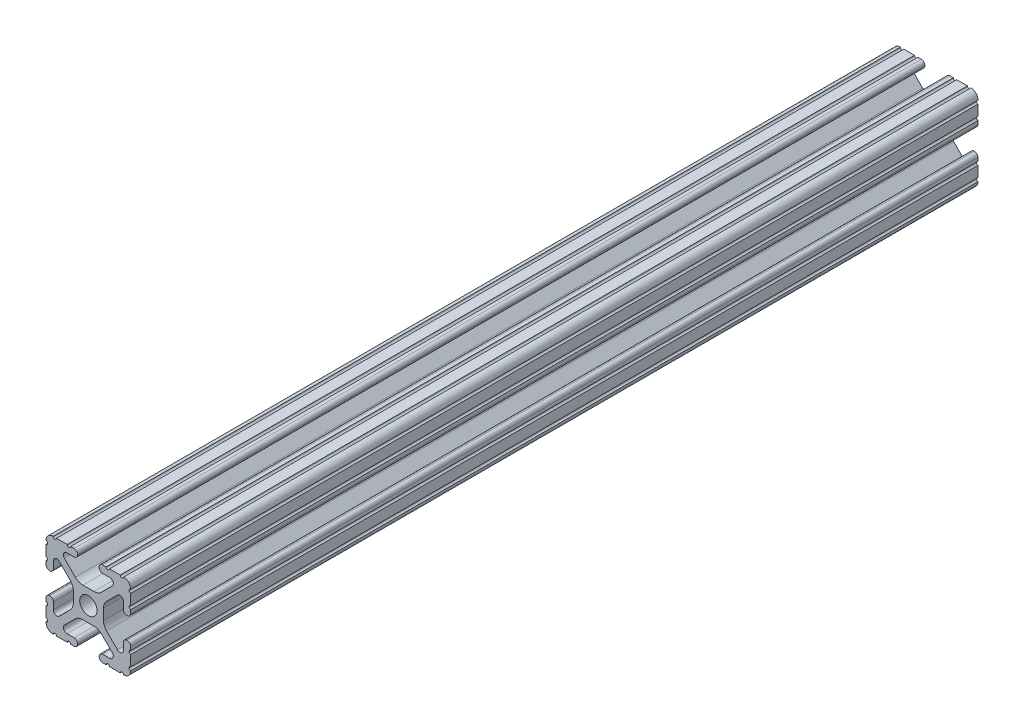
SolidWorks part; units mm, degrees
ref_plane "Front Plane" through (0, 0, 0) normal (0, 0, 1) x (1, 0, 0)
ref_plane "Top Plane" through (0, 0, 0) normal (0, 1, 0) x (1, 0, 0)
ref_plane "Right Plane" through (0, 0, 0) normal (1, 0, 0) x (0, 0, -1)
sketch "Sketch1" plane through (0, 0, 0) normal (0, 0, 1) x (1, 0, 0)
  line L88 (-7.1797, -8.6452) -> (-3.9523, -5.4237)
  line L89 (-1.7093, -4.4958) -> (1.7093, -4.4958)
  line L90 (3.9523, -5.4237) -> (7.1797, -8.6452)
  line L91 (6.4164, -10.4902) -> (4.2875, -10.4902)
  line L92 (3.2385, -11.5392) -> (3.2385, -11.651)
  line L93 (4.2875, -12.7) -> (5.3171, -12.7)
  line L94 (6.3331, -12.7) -> (9.5504, -12.7)
  line L95 (12.7, -9.5504) -> (12.7, -6.3331)
  line L96 (12.7, -5.3171) -> (12.7, -4.2875)
  line L97 (11.651, -3.2385) -> (11.5392, -3.2385)
  line L98 (10.4902, -4.2875) -> (10.4902, -6.4021)
  line L99 (8.7371, -7.1294) -> (5.441, -3.8408)
  line L100 (4.5085, -1.5932) -> (4.5085, 1.5932)
  line L101 (5.441, 3.8408) -> (8.7371, 7.1294)
  line L102 (10.4902, 6.4021) -> (10.4902, 4.2875)
  line L103 (11.5392, 3.2385) -> (11.651, 3.2385)
  line L104 (12.7, 4.2875) -> (12.7, 5.3171)
  line L105 (12.7, 6.3331) -> (12.7, 9.5504)
  line L106 (9.5504, 12.7) -> (6.3331, 12.7)
  line L107 (5.3171, 12.7) -> (4.2875, 12.7)
  line L108 (3.2385, 11.651) -> (3.2385, 11.5392)
  line L109 (4.2875, 10.4902) -> (6.4768, 10.4902)
  line L110 (7.207, 8.7244) -> (3.8983, 5.4232)
  line L111 (1.6558, 4.4958) -> (-1.6558, 4.4958)
  line L112 (-3.8983, 5.4232) -> (-7.207, 8.7244)
  line L113 (-6.4768, 10.4902) -> (-4.2875, 10.4902)
  line L114 (-3.2385, 11.5392) -> (-3.2385, 11.651)
  line L115 (-4.2875, 12.7) -> (-5.3171, 12.7)
  line L116 (-6.3331, 12.7) -> (-9.5504, 12.7)
  line L117 (-12.7, 9.5504) -> (-12.7, 6.3331)
  line L118 (-12.7, 5.3171) -> (-12.7, 4.2875)
  line L119 (-11.651, 3.2385) -> (-11.5392, 3.2385)
  line L120 (-10.4902, 4.2875) -> (-10.4902, 6.4021)
  line L121 (-8.7371, 7.1294) -> (-5.441, 3.8408)
  line L122 (-4.5085, 1.5932) -> (-4.5085, -1.5932)
  line L123 (-5.441, -3.8408) -> (-8.7371, -7.1294)
  line L124 (-10.4902, -6.4021) -> (-10.4902, -4.2875)
  line L125 (-11.5392, -3.2385) -> (-11.651, -3.2385)
  line L126 (-12.7, -4.2875) -> (-12.7, -5.3171)
  line L127 (-12.7, -6.3331) -> (-12.7, -9.5504)
  line L128 (-9.5504, -12.7) -> (-6.3331, -12.7)
  line L129 (-5.3171, -12.7) -> (-4.2875, -12.7)
  line L130 (-3.2385, -11.651) -> (-3.2385, -11.5392)
  line L131 (-4.2875, -10.4902) -> (-6.4164, -10.4902)
  circle A1 centre (0, 0) radius 2.6035
  arc A104 (-7.1797, -8.6452) -> (-6.4164, -10.4902) centre (-6.4164, -9.4098) ccw
  arc A105 (-1.7093, -4.4958) -> (-3.9523, -5.4237) centre (-1.7093, -7.6708) ccw
  arc A106 (3.9523, -5.4237) -> (1.7093, -4.4958) centre (1.7093, -7.6708) ccw
  arc A107 (6.4164, -10.4902) -> (7.1797, -8.6452) centre (6.4164, -9.4098) ccw
  arc A108 (4.2875, -10.4902) -> (3.2385, -11.5392) centre (4.2875, -11.5392) ccw
  arc A109 (3.2385, -11.651) -> (4.2875, -12.7) centre (4.2875, -11.651) ccw
  arc A110 (6.3331, -12.7) -> (5.3171, -12.7) centre (5.8251, -12.7) ccw
  arc A111 (10.5664, -12.6998) -> (9.5504, -12.7) centre (10.0584, -12.7) ccw
  arc A112 (10.5664, -12.6998) -> (12.6998, -10.5664) centre (10.5918, -10.5918) ccw
  arc A113 (12.7, -9.5504) -> (12.6998, -10.5664) centre (12.7, -10.0584) ccw
  arc A114 (12.7, -5.3171) -> (12.7, -6.3331) centre (12.7, -5.8251) ccw
  arc A115 (12.7, -4.2875) -> (11.651, -3.2385) centre (11.651, -4.2875) ccw
  arc A116 (11.5392, -3.2385) -> (10.4902, -4.2875) centre (11.5392, -4.2875) ccw
  arc A117 (8.7371, -7.1294) -> (10.4902, -6.4021) centre (9.4628, -6.4021) ccw
  arc A118 (4.5085, -1.5932) -> (5.441, -3.8408) centre (7.6835, -1.5932) ccw
  arc A119 (5.441, 3.8408) -> (4.5085, 1.5932) centre (7.6835, 1.5932) ccw
  arc A120 (10.4902, 6.4021) -> (8.7371, 7.1294) centre (9.4628, 6.4021) ccw
  arc A121 (10.4902, 4.2875) -> (11.5392, 3.2385) centre (11.5392, 4.2875) ccw
  arc A122 (11.651, 3.2385) -> (12.7, 4.2875) centre (11.651, 4.2875) ccw
  arc A123 (12.7, 6.3331) -> (12.7, 5.3171) centre (12.7, 5.8251) ccw
  arc A124 (12.6998, 10.5664) -> (12.7, 9.5504) centre (12.7, 10.0584) ccw
  arc A125 (12.6998, 10.5664) -> (10.5664, 12.6998) centre (10.5918, 10.5918) ccw
  arc A126 (9.5504, 12.7) -> (10.5664, 12.6998) centre (10.0584, 12.7) ccw
  arc A127 (5.3171, 12.7) -> (6.3331, 12.7) centre (5.8251, 12.7) ccw
  arc A128 (4.2875, 12.7) -> (3.2385, 11.651) centre (4.2875, 11.651) ccw
  arc A129 (3.2385, 11.5392) -> (4.2875, 10.4902) centre (4.2875, 11.5392) ccw
  arc A130 (7.207, 8.7244) -> (6.4768, 10.4902) centre (6.4768, 9.4563) ccw
  arc A131 (1.6558, 4.4958) -> (3.8983, 5.4232) centre (1.6558, 7.6708) ccw
  arc A132 (-3.8983, 5.4232) -> (-1.6558, 4.4958) centre (-1.6558, 7.6708) ccw
  arc A133 (-6.4768, 10.4902) -> (-7.207, 8.7244) centre (-6.4768, 9.4563) ccw
  arc A134 (-4.2875, 10.4902) -> (-3.2385, 11.5392) centre (-4.2875, 11.5392) ccw
  arc A135 (-3.2385, 11.651) -> (-4.2875, 12.7) centre (-4.2875, 11.651) ccw
  arc A136 (-6.3331, 12.7) -> (-5.3171, 12.7) centre (-5.8251, 12.7) ccw
  arc A137 (-10.5664, 12.6998) -> (-9.5504, 12.7) centre (-10.0584, 12.7) ccw
  arc A138 (-10.5664, 12.6998) -> (-12.6998, 10.5664) centre (-10.5918, 10.5918) ccw
  arc A139 (-12.7, 9.5504) -> (-12.6998, 10.5664) centre (-12.7, 10.0584) ccw
  arc A140 (-12.7, 5.3171) -> (-12.7, 6.3331) centre (-12.7, 5.8251) ccw
  arc A141 (-12.7, 4.2875) -> (-11.651, 3.2385) centre (-11.651, 4.2875) ccw
  arc A142 (-11.5392, 3.2385) -> (-10.4902, 4.2875) centre (-11.5392, 4.2875) ccw
  arc A143 (-8.7371, 7.1294) -> (-10.4902, 6.4021) centre (-9.4628, 6.4021) ccw
  arc A144 (-4.5085, 1.5932) -> (-5.441, 3.8408) centre (-7.6835, 1.5932) ccw
  arc A145 (-5.441, -3.8408) -> (-4.5085, -1.5932) centre (-7.6835, -1.5932) ccw
  arc A146 (-10.4902, -6.4021) -> (-8.7371, -7.1294) centre (-9.4628, -6.4021) ccw
  arc A147 (-10.4902, -4.2875) -> (-11.5392, -3.2385) centre (-11.5392, -4.2875) ccw
  arc A148 (-11.651, -3.2385) -> (-12.7, -4.2875) centre (-11.651, -4.2875) ccw
  arc A149 (-12.7, -6.3331) -> (-12.7, -5.3171) centre (-12.7, -5.8251) ccw
  arc A150 (-12.6998, -10.5664) -> (-12.7, -9.5504) centre (-12.7, -10.0584) ccw
  arc A151 (-12.6998, -10.5664) -> (-10.5664, -12.6998) centre (-10.5918, -10.5918) ccw
  arc A152 (-9.5504, -12.7) -> (-10.5664, -12.6998) centre (-10.0584, -12.7) ccw
  arc A153 (-5.3171, -12.7) -> (-6.3331, -12.7) centre (-5.8251, -12.7) ccw
  arc A154 (-4.2875, -12.7) -> (-3.2385, -11.651) centre (-4.2875, -11.651) ccw
  arc A155 (-3.2385, -11.5392) -> (-4.2875, -10.4902) centre (-4.2875, -11.5392) ccw
extrude "Boss-Extrude1" add sketch "Sketch1" along normal mid plane 254
